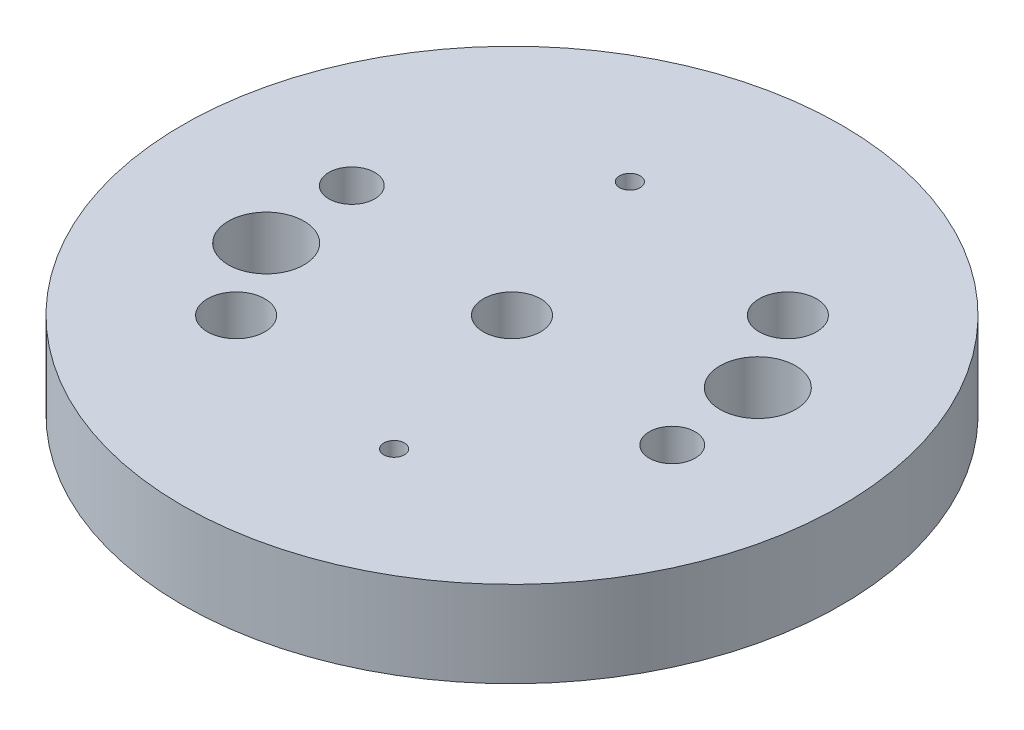
SolidWorks part; units mm, degrees
material "Gray Cast Iron"
ref_plane "Front Plane" through (0, 0, 0) normal (0, 0, 1) x (1, 0, 0)
ref_plane "Top Plane" through (0, 0, 0) normal (0, 1, 0) x (1, 0, 0)
ref_plane "Right Plane" through (0, 0, 0) normal (1, 0, 0) x (0, 0, -1)
sketch "Sketch1" plane through (0, 0, 0) normal (0, 1, 0) x (1, 0, 0)
  circle A0 centre (0, 0) radius 36.4744
  dimension "D1" = 72.9488
extrude "Boss-Extrude1" add sketch "Sketch1" against normal blind 9.525
sketch "Sketch2" plane through (0, -9.525, 0) normal (0, -1, 0) x (1, 0, 0)
  circle A0 centre (0, 0) radius 26.543
  dimension "D1" = 53.086
extrude "Boss-Extrude2" add sketch "Sketch2" along normal blind 3.175
sketch "Sketch5" plane through (0, 0, 0) normal (0, 1, 0) x (1, 0, 0)
  line L0 (0, 0) -> (58.6469, 0) construction
  line L1 (-21.8754, 3.6607) -> (49292.4047, -8248.7196) construction
  line L2 (20.6741, 20.6741) -> (-35334.665, -35334.665) construction
  line L3 (-7.0641, 21.7412) -> (15443.7856, -47531.0847) construction
  line L4 (-19.9933, -6.4962) -> (47532.8325, 15444.3535) construction
  circle A0 centre (0, 0) radius 3.175
  circle A1 centre (-6.2792, 19.3255) radius 1.143
  circle A3 centre (-20.5333, -6.6717) radius 4.191
  circle A5 centre (-15.2664, -15.2664) radius 3.175
  circle A8 centre (15.2664, 15.2664) radius 3.175
  circle A9 centre (6.2792, -19.3255) radius 1.143
  circle A10 centre (20.5333, 6.6717) radius 4.191
  circle A11 centre (21.2939, -3.5634) radius 2.54
  circle A12 centre (-21.2939, 3.5634) radius 2.54
  dimension "D1" = 6.35
  dimension "D2" = 2.286
  dimension "D3" = 2.286
  dimension "D4" = 6.35
  dimension "D5" = 6.35
  dimension "D7" = 20.32
  dimension "D8" = 21.59
  dimension "D12" = 8.382
  dimension "D13" = 5.08
  dimension "D14" = 8.382
  dimension "D15" = 5.08
  dimension "D16" = 21.59
  dimension "D19" = 21.59
  dimension "D20" = 62.5
  dimension "D22" = 90
  dimension "D6" = 20.32
  dimension "D9" = 21.59
  dimension "D10" = 45
  dimension "D11" = 63
  dimension "D17" = 21.59
  dimension "D18" = 21.59
extrude "Cut-Extrude1" cut sketch "Sketch5" against normal through all
